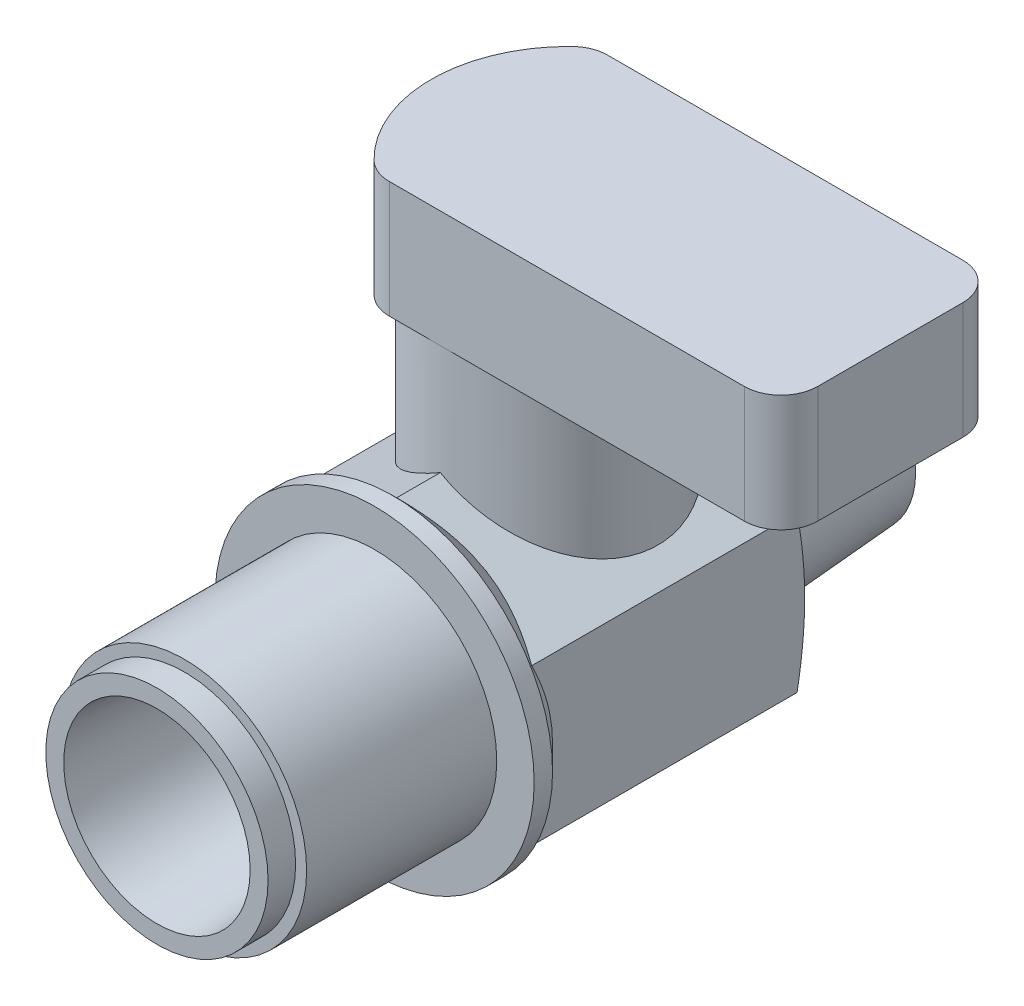
SolidWorks part; units mm, degrees
ref_plane "Front Plane" through (0, 0, 0) normal (0, 0, 1) x (1, 0, 0)
ref_plane "Top Plane" through (0, 0, 0) normal (0, 1, 0) x (1, 0, 0)
ref_plane "Right Plane" through (0, 0, 0) normal (1, 0, 0) x (0, 0, -1)
sketch "Sketch2" plane through (0, 0, 0) normal (0, 0, 1) x (1, 0, 0)
  line L1 (0, 8.6228) -> (-7.4676, 4.3114)
  line L2 (-7.4676, 4.3114) -> (-7.4676, -4.3114)
  line L3 (-7.4676, -4.3114) -> (0, -8.6228)
  line L4 (0, -8.6228) -> (7.4676, -4.3114)
  line L5 (7.4676, -4.3114) -> (7.4676, 4.3114)
  line L6 (7.4676, 4.3114) -> (0, 8.6228)
  circle A0 centre (0, 0) radius 7.4676 construction
  dimension "D1" = 14.9352
extrude "Boss-Extrude1" add sketch "Sketch2" along normal blind 45.72
sketch "Sketch1" plane through (0, 0, 0) normal (1, 0, 0) x (0, 0, -1)
  line L0 (8.7223, 0) -> (8.7223, 28.9673)
  line L1 (-37.4396, 6.1468) -> (-35.9156, 6.1468)
  line L2 (-9.0424, 7.366) -> (-9.0424, 5.1562)
  line L3 (-9.0424, 5.1562) -> (0, 4.5239)
  line L4 (8.7223, 0) -> (16.4423, 0) construction
  line L5 (-9.0424, 7.366) -> (-12.8722, 17.8882)
  line L6 (0, 4.5239) -> (0, 2.5781)
  line L7 (0, 2.5781) -> (-2.5781, 2.5781)
  line L8 (-2.5781, 2.5781) -> (-2.5781, 0)
  line L9 (-2.5781, 0) -> (8.7223, 0)
  line L10 (-12.8722, 17.8882) -> (-25.4, 17.8882)
  line L12 (-37.4396, 6.1468) -> (-37.4396, 5.1562)
  line L13 (-37.4396, 5.1562) -> (-28.3972, 4.5239)
  line L14 (-28.3972, 4.5239) -> (-28.3972, 0)
  line L15 (-28.3972, 0) -> (-61.3139, 0)
  line L16 (-61.3139, 0) -> (-61.3139, 28.9673)
  line L17 (-61.3139, 28.9673) -> (8.7223, 28.9673)
  line L18 (-35.9156, 6.1468) -> (-35.9156, 6.7564)
  line L19 (-35.9156, 6.7564) -> (-25.4, 6.7564)
  line L20 (-25.4, 6.7564) -> (-25.4, 17.8882)
  dimension "D1" = 0.6096
  dimension "D2" = 4
  dimension "D3" = 9.0424
  dimension "D4" = 10.3124
  dimension "D5" = 5.1562
  dimension "D6" = 70
  dimension "D7" = 13.5128
  dimension "D8" = 14.732
  dimension "D9" = 28.3972
  dimension "D10" = 1.524
  dimension "D11" = 25.4
revolve "Cut-Revolve1" cut sketch "Sketch1" angle 360 about L4
sketch "Sketch4" plane through (0, 0, 0) normal (1, 0, 0) x (0, 0, -1)
  line L0 (-25.4, 8.826) -> (-24.384, 8.826)
  line L1 (-24.384, 8.826) -> (-19.4793, 3.9214)
  line L2 (-19.4793, 3.9214) -> (-25.4, 3.9214)
  line L3 (-25.4, 3.9214) -> (-25.4, 8.826)
  line L4 (-13.2324, 0) -> (-6.6362, 0) construction
  line L5 (-25.4, 8.6228) -> (-9.4999, 8.6228) construction
  line L6 (-25.4, 6.7564) -> (-25.4, 17.8882) construction
  dimension "D1" = 17.6521
  dimension "D2" = 1.016
  dimension "D3" = 45
  dimension "D4" = 0.2032
revolve "Revolve1" add sketch "Sketch4" angle 360 about L4
sketch "Sketch5" plane through (0, 0, 0) normal (0, 1, 0) x (1, 0, 0)
  circle A0 centre (0, -15.748) radius 6.0198
  dimension "D1" = 12.0396
  dimension "D2" = 15.748
extrude "Boss-Extrude3" add sketch "Sketch5" along normal blind 14.732
sketch "Sketch6" plane through (0, 14.732, 0) normal (0, 1, 0) x (1, 0, 0)
  line L0 (-2.7962, -21.7932) -> (16.8402, -21.7932)
  line L1 (18.8722, -19.7612) -> (18.8722, -11.7348)
  line L2 (16.8402, -9.7028) -> (-2.7962, -9.7028)
  circle A0 centre (0, -15.748) radius 6.0198 construction
  arc A1 (-4.2102, -10.2755) -> (-4.2102, -21.2205) centre (1.0922, -15.748) ccw
  arc A2 (16.8402, -21.7932) -> (18.8722, -19.7612) centre (16.8402, -19.7612) ccw
  arc A3 (-4.2102, -21.2205) -> (-2.7962, -21.7932) centre (-2.7962, -19.7612) ccw
  arc A4 (-2.7962, -9.7028) -> (-4.2102, -10.2755) centre (-2.7962, -11.7348) ccw
  arc A5 (18.8722, -11.7348) -> (16.8402, -9.7028) centre (16.8402, -11.7348) ccw
  point P17 (-6.5278, -15.748)
  dimension "D2" = 7.62
  dimension "D3" = 0.508
  dimension "D4" = 25.4
  dimension "D5" = 2.032
  dimension "D1" = 12.0904
extrude "Boss-Extrude4" add sketch "Sketch6" along normal blind 6.4516
